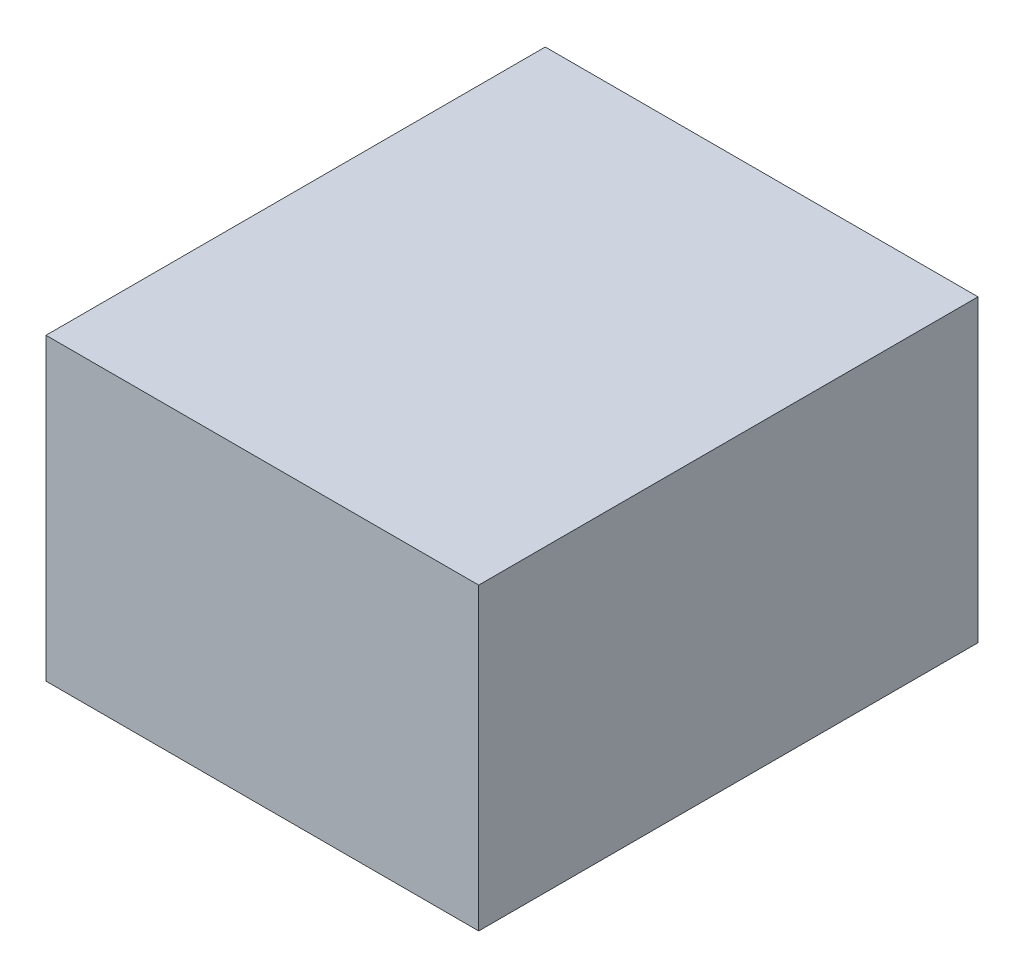
SolidWorks part; units mm, degrees
material "Plastique personnalisé"
ref_plane "Plan de face" through (0, 0, 0) normal (0, 0, 1) x (1, 0, 0)
ref_plane "Plan de dessus" through (0, 0, 0) normal (0, 1, 0) x (1, 0, 0)
ref_plane "Plan de droite" through (0, 0, 0) normal (1, 0, 0) x (0, 0, -1)
sketch "Esquisse1" plane through (0, 0, 0) normal (0, 1, 0) x (1, 0, 0)
  line L0 (6.8735, 12.2076) -> (3.8735, 12.2076)
  line L1 (3.8735, 12.2076) -> (6.8735, 12.2076)
  line L2 (-3.1265, -12.7924) -> (-3.1265, -17.7924)
  line L3 (-3.1265, -17.7924) -> (6.8735, -17.7924)
  line L5 (-3.1265, -17.7924) -> (-3.1265, -12.7924)
  line L6 (12.8735, 12.2076) -> (15.8735, 12.2076)
  line L8 (6.8735, 12.2076) -> (12.8735, 12.2076)
  line L12 (12.8735, -17.7924) -> (6.8735, -17.7924)
  line L13 (-3.1265, -12.7924) -> (-3.1265, 12.2076)
  line L14 (-3.1265, 12.2076) -> (3.8735, 12.2076)
  line L15 (22.8735, -17.7924) -> (12.8735, -17.7924)
  line L16 (22.8735, -12.7924) -> (22.8735, -17.7924)
  line L17 (22.8735, -12.7924) -> (22.8735, 12.2076)
  line L18 (22.8735, 12.2076) -> (15.8735, 12.2076)
  dimension "D1" = 30
  dimension "D3" = 3
  dimension "D4" = 5
extrude "Boss.-Extru.1" add sketch "Esquisse1" along normal blind 18
